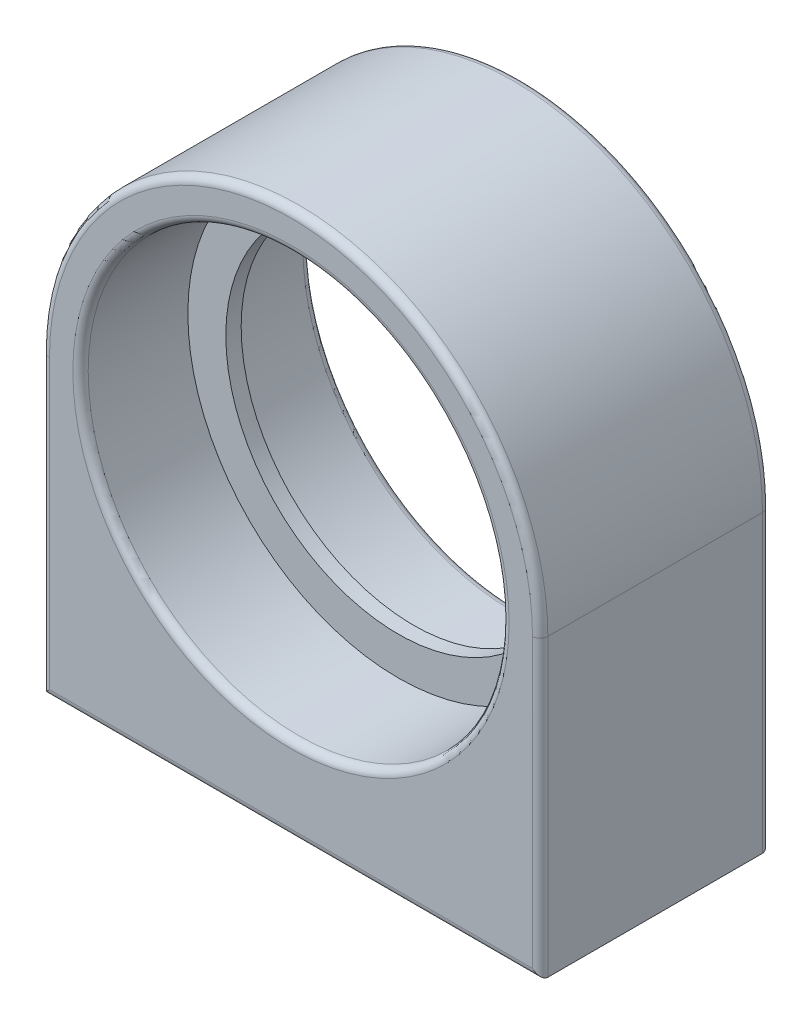
SolidWorks part; units mm, degrees
ref_plane "Ebene vorne" through (0, 0, 0) normal (0, 0, 1) x (1, 0, 0)
ref_plane "Ebene oben" through (0, 0, 0) normal (0, 1, 0) x (1, 0, 0)
ref_plane "Ebene rechts" through (0, 0, 0) normal (1, 0, 0) x (0, 0, -1)
sketch "Skizze1" plane through (0, 0, 0) normal (0, 0, 1) x (1, 0, 0)
  line L0 (0, 51.75) -> (-6.6729, 51.75) construction
  line L1 (-32.5, -19.25) -> (32.5, -19.25)
  line L2 (-32.5, -19.25) -> (-32.5, 19.25)
  line L3 (-32.5, 19.25) -> (32.5, 19.25)
  line L4 (32.5, -19.25) -> (32.5, 19.25)
  line L5 (-32.5, -19.25) -> (32.5, 19.25) construction
  line L6 (-32.5, 19.25) -> (32.5, -19.25) construction
  circle A0 centre (0, 19.25) radius 32.5
  circle A1 centre (0, 19.25) radius 22.5
  point P0 (0, 0)
  dimension "D3" = 45
  dimension "D1" = 71
  dimension "D2" = 65
extrude "Aufsatz-Linear austragen1" add sketch "Skizze1" along normal mid plane 30 contours A1 L3 A0 | A1 L3 A0 | A0 L2 L1 L4
sketch "Skizze3" plane through (0, 0, 15) normal (0, 0, 1) x (1, 0, 0)
  circle A0 centre (0, 19.25) radius 27.45
  dimension "D1" = 54.9
extrude "Schnitt-Linear austragen1" cut sketch "Skizze3" against normal blind 14
mirror "Spiegeln1" about plane through (0, 0, 0) normal (0, 0, 1) of "Schnitt-Linear austragen1"
sketch "Skizze4" plane through (0, -19.25, 0) normal (0, -1, 0) x (1, 0, 0)
  line L0 (-32.5, 0) -> (32.5, 0) construction
  line L1 (-32.5, 15) -> (-32.5, -15) construction
  line L2 (32.5, 15) -> (32.5, -15) construction
  line L3 (-32.5, 0) -> (-22.5, 0) construction
  line L4 (0, 0) -> (0, 6.6092) construction
  circle A0 centre (-22.5, 0) radius 2.8
  circle A1 centre (-10, 0) radius 2.8
  circle A2 centre (10, 0) radius 2.8
  circle A3 centre (22.5, 0) radius 2.8
  dimension "D3" = 5.6
  dimension "D4" = 5.6
  dimension "D1" = 10
  dimension "D2" = 12.5
extrude "Schnitt-Linear austragen2" cut sketch "Skizze4" against normal blind 11
fillet "Verrundung1" radius 1 14 edges at (-32.5, 0, -15) (-32.5, 0, 15) (0, -19.25, -15) (0, -19.25, 15) (32.5, 0, -15) (32.5, 0, 15) (0, 51.75, -15) (0, 51.75, 15) (27.45, 19.25, -15) (27.45, 19.25, 15) (22.5, -19.25, 2.8) (10, -19.25, 2.8) (-10, -19.25, -2.8) (-22.5, -19.25, -2.8)
